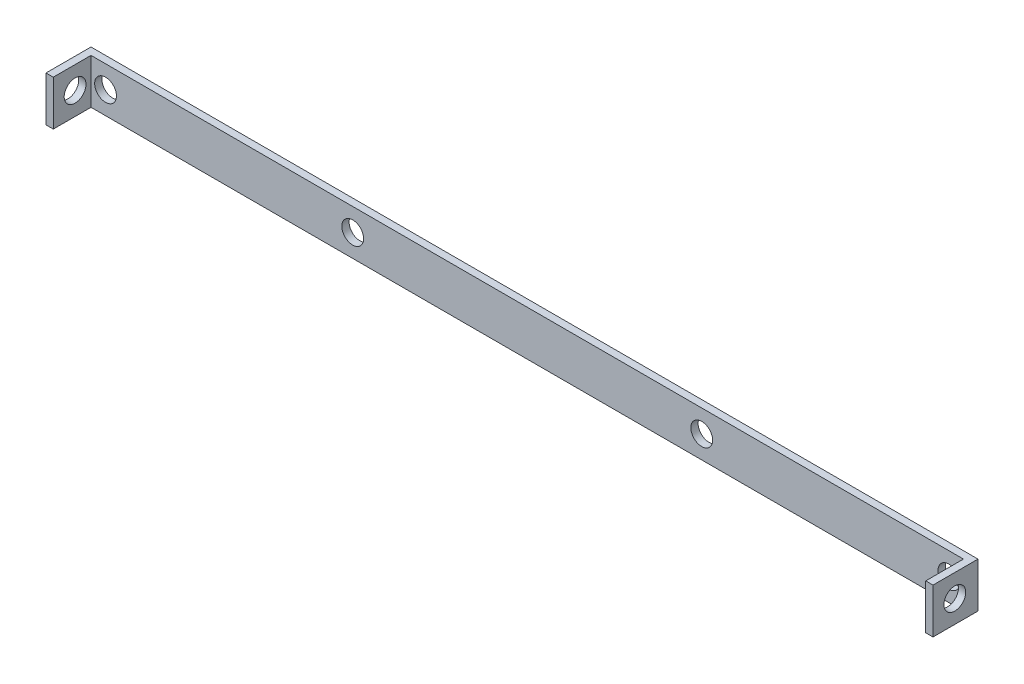
SolidWorks part; units mm, degrees
material "7075-O (SS)"
ref_plane "Front Plane" through (0, 0, 0) normal (0, 0, 1) x (1, 0, 0)
ref_plane "Top Plane" through (0, 0, 0) normal (0, 1, 0) x (1, 0, 0)
ref_plane "Right Plane" through (0, 0, 0) normal (1, 0, 0) x (0, 0, -1)
sketch "Sketch1" plane through (0, 0, 0) normal (0, 0, 1) x (1, 0, 0)
  line L5 (-48.4125, -2.4562) -> (48.4125, -2.4562)
  line L6 (-48.4125, -2.4562) -> (-48.4125, 2.4563)
  line L7 (-48.4125, 2.4563) -> (48.4125, 2.4563)
  line L8 (48.4125, -2.4562) -> (48.4125, 2.4563)
  line L9 (-48.4125, -2.4562) -> (48.4125, 2.4563) construction
  line L10 (-48.4125, 2.4563) -> (48.4125, -2.4562) construction
  point P0 (0, 0)
  dimension "D1" = 4.9125
  dimension "D2" = 96.825
extrude "Boss-Extrude1" add sketch "Sketch1" along normal blind 4.9125
shell "Shell1" thickness 0.7937
sketch "Sketch2" plane through (0, 0, 0.7937) normal (0, 0, 1) x (1, 0, 0)
  line L0 (-48.4125, 2.4563) -> (-48.4125, -2.4562) construction
  line L1 (48.4125, -2.4562) -> (48.4125, 2.4563) construction
  line L2 (0, -55) -> (0, 55) construction
  line L3 (55, 0) -> (-55, 0) construction
  circle A0 centre (-46.0312, 0) radius 1.1906
  circle A4 centre (-19.05, 0) radius 1.1906
  circle A5 centre (19.05, 0) radius 1.1906
  circle A6 centre (46.0313, 0) radius 1.1906
  point P4 (0, 0)
  point P9 (0, 0)
  point P16 (0, 0)
  dimension "D1" = 2.3813
  dimension "D2" = 2.3813
  dimension "D3" = 2.3813
  dimension "D4" = 2.3813
  dimension "D5" = 2.3813
  dimension "D6" = 2.3813
  dimension "D7" = 19.05
  dimension "D8" = 19.05
extrude "Cut-Extrude1" cut sketch "Sketch2" against normal through all
sketch "Sketch3" plane through (-48.4125, 0, 0) normal (-1, 0, 0) x (0, 0, 1)
  line L0 (2.7019, 0) -> (-2.7019, 0) construction
  line L1 (4.9125, 2.4563) -> (4.9125, -2.4562) construction
  circle A0 centre (2.5312, 0) radius 1.1906
  dimension "D1" = 2.3813
  dimension "D2" = 2.3813
extrude "Cut-Extrude2" cut sketch "Sketch3" against normal through all
